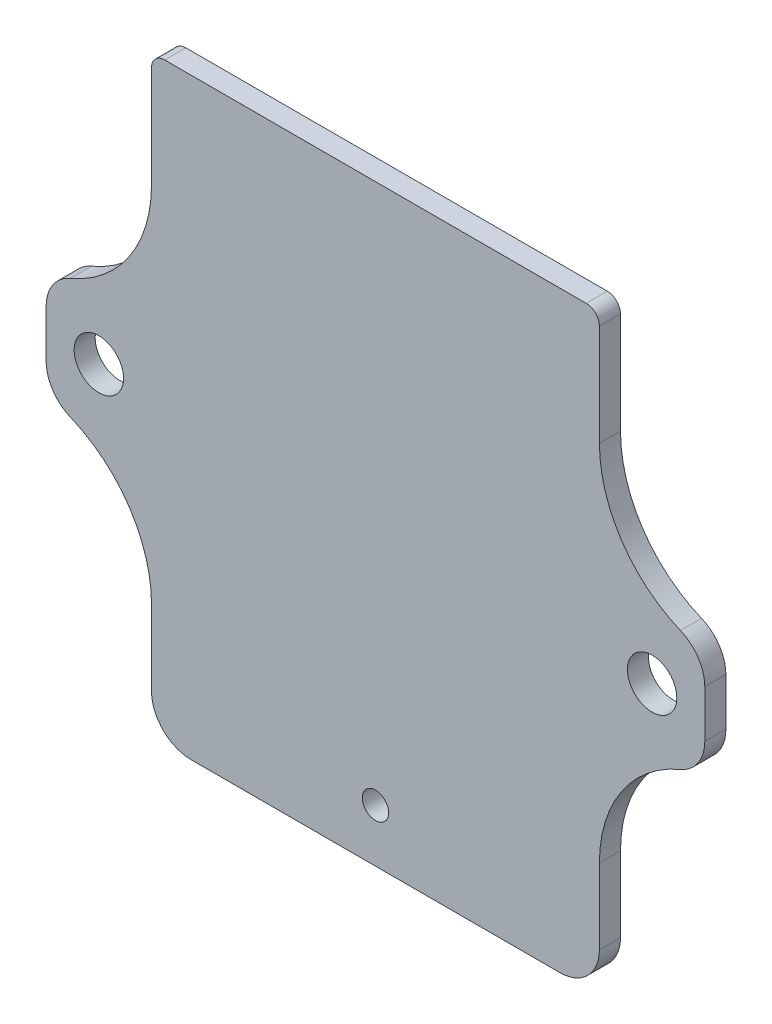
SolidWorks part; units mm, degrees
ref_plane "Front Plane" through (0, 0, 0) normal (0, 0, 1) x (1, 0, 0)
ref_plane "Top Plane" through (0, 0, 0) normal (0, 1, 0) x (1, 0, 0)
ref_plane "Right Plane" through (0, 0, 0) normal (1, 0, 0) x (0, 0, -1)
sketch "Sketch1" plane through (0, 0, 0) normal (0, 0, 1) x (1, 0, 0)
  line L0 (30.8838, 108.1349) -> (30.8838, 115.8369)
  line L1 (29.8838, 116.8369) -> (-2.1162, 116.8369)
  line L2 (-3.1162, 115.8369) -> (-3.1162, 108.1349)
  line L3 (-11.1162, 96.1349) -> (-11.1162, 92.539)
  line L4 (-3.1162, 80.539) -> (-3.1162, 74.8369)
  line L5 (-0.1162, 71.8369) -> (27.8838, 71.8369)
  line L6 (30.8838, 74.8369) -> (30.8838, 80.539)
  line L7 (38.8838, 92.539) -> (38.8838, 96.1349)
  circle A0 centre (13.8838, 75.8369) radius 1
  circle A1 centre (-7.1162, 94.3369) radius 1.875
  circle A2 centre (34.8838, 94.3369) radius 1.875
  arc A3 (30.8838, 115.8369) -> (29.8838, 116.8369) centre (29.8838, 115.8369) ccw
  arc A4 (-2.1162, 116.8369) -> (-3.1162, 115.8369) centre (-2.1162, 115.8369) ccw
  arc A5 (-9.2701, 98.9041) -> (-3.1162, 108.1349) centre (-13.1162, 108.1349) ccw
  arc A6 (-9.2701, 98.9041) -> (-11.1162, 96.1349) centre (-8.1162, 96.1349) ccw
  arc A7 (-11.1162, 92.539) -> (-9.2701, 89.7697) centre (-8.1162, 92.539) ccw
  arc A8 (-3.1162, 80.539) -> (-9.2701, 89.7697) centre (-13.1162, 80.539) ccw
  arc A9 (-3.1162, 74.8369) -> (-0.1162, 71.8369) centre (-0.1162, 74.8369) ccw
  arc A10 (27.8838, 71.8369) -> (30.8838, 74.8369) centre (27.8838, 74.8369) ccw
  arc A11 (37.0376, 89.7697) -> (30.8838, 80.539) centre (40.8838, 80.539) ccw
  arc A12 (37.0376, 89.7697) -> (38.8838, 92.539) centre (35.8838, 92.539) ccw
  arc A13 (38.8838, 96.1349) -> (37.0376, 98.9041) centre (35.8838, 96.1349) ccw
  arc A14 (30.8838, 108.1349) -> (37.0376, 98.9041) centre (40.8838, 108.1349) ccw
extrude "Boss-Extrude1" add sketch "Sketch1" along normal blind 1.6
